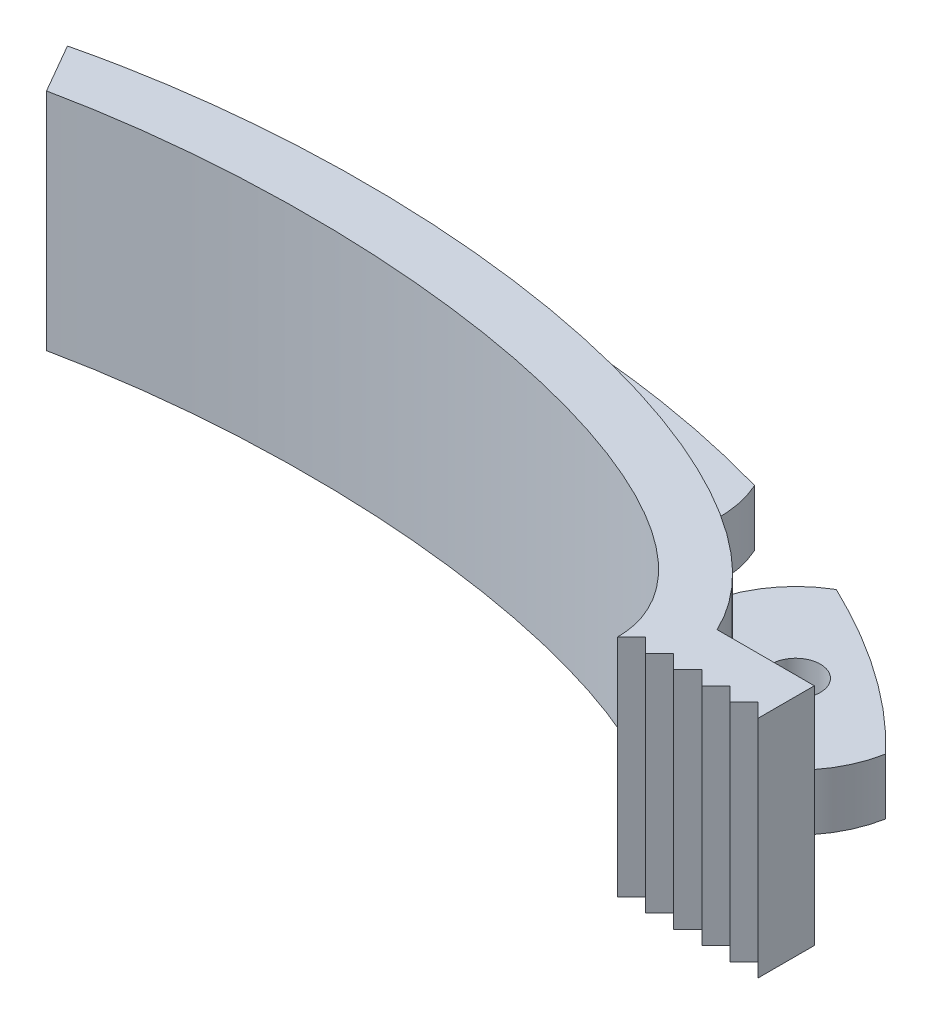
SolidWorks part; units mm, degrees
ref_plane "Спереди" through (0, 0, 0) normal (0, 0, 1) x (1, 0, 0)
ref_plane "Сверху" through (0, 0, 0) normal (0, 1, 0) x (1, 0, 0)
ref_plane "Справа" through (0, 0, 0) normal (1, 0, 0) x (0, 0, -1)
sketch "Эскиз1" plane through (0, 0, 0) normal (0, 1, 0) x (1, 0, 0)
  line L0 (0, 0) -> (56.8008, 26.4866) construction
  line L1 (0, 0) -> (22.8944, 39.6542) construction
  line L2 (0, 0) -> (-19.5543, 33.869) construction
  line L3 (0, 0) -> (57.6145, 0) construction
  line L4 (-20.1743, 18.9429) -> (-18.9654, 16.8451)
  line L5 (42.2674, 4) -> (40.0811, 4)
  circle A0 centre (33.8772, 15.7972) radius 1.75
  circle A1 centre (13.2428, 22.9372) radius 1.75
  circle A2 centre (-13.2428, 22.9372) radius 1.75
  arc A3 (-5.3565, 21.5932) -> (-20.1743, 18.9429) centre (-13.2428, 22.9372) ccw
  arc A4 (38.7397, 9.4445) -> (26.0244, 17.3244) centre (33.8772, 15.7972) ccw
  arc A6 (20.3072, 19.1829) -> (5.3565, 21.5932) centre (13.2428, 22.9372) ccw
  ellipse E0 centre (0, 0) end of major axis (45, 0) minor radius 24 construction
  ellipse E1 centre (0, 0) end of major axis (-41, 0) minor radius 19 (40.0811, 4) -> (-18.9654, 16.8451) ccw
  ellipse E2 centre (0, 0) end of major axis (43, 0) minor radius 21.7627 (-5.3565, 21.5932) -> (5.3565, 21.5932) cw
  ellipse E3 centre (0, 0) end of major axis (43, 0) minor radius 21.7627 (20.3072, 19.1829) -> (26.0244, 17.3244) cw
  ellipse E4 centre (0, 0) end of major axis (45, 0) minor radius 24 (11.5128, 23.2013) -> (14.9663, 22.6338) cw construction
  ellipse E5 centre (0, 0) end of major axis (43, 0) minor radius 21.7627 (38.7397, 9.4445) -> (42.2674, 4) cw
  dimension "D6" = 19
  dimension "D7" = 4
  dimension "D1" = 45
  dimension "D2" = 24
  dimension "D3" = 25
  dimension "D4" = 60
  dimension "D5" = 120
extrude "Бобышка-Вытянуть1" add sketch "Эскиз1" along normal blind 4
sketch "Эскиз2" plane through (0, 4, 0) normal (0, 1, 0) x (1, 0, 0)
  line L0 (37, 0) -> (47, 0) construction
  line L1 (47, 0) -> (47, 4)
  line L2 (47, 4) -> (40.0811, 4)
  line L3 (-18.9654, 16.8451) -> (-16.9427, 13.335)
  line L4 (45, 1) -> (47, 1) construction
  line L5 (47, 0) -> (46, 1)
  line L6 (46, 1) -> (45, 0)
  line L7 (44, 1) -> (43, 0)
  line L8 (45, 0) -> (44, 1)
  line L9 (42, 1) -> (41, 0)
  line L10 (43, 0) -> (42, 1)
  line L11 (40, 1) -> (39, 0)
  line L12 (41, 0) -> (40, 1)
  line L13 (38, 1) -> (37, 0)
  line L14 (39, 0) -> (38, 1)
  ellipse E0 centre (0, 0) end of major axis (-37, 0) minor radius 15 construction
  ellipse E1 centre (0, 0) end of major axis (-37, 0) minor radius 15 (37, 0) -> (-16.9427, 13.335) ccw
  ellipse E2 centre (0, 0) end of major axis (-41, 0) minor radius 19 (40.0811, 4) -> (-18.9654, 16.8451) ccw
  dimension "D5" = 4
  dimension "D1" = 4
  dimension "D2" = 10
  dimension "D3" = 37
  dimension "D4" = 15
  dimension "D6" = 1
  dimension "D7" = 5
extrude "Бобышка-Вытянуть2" add sketch "Эскиз2" along normal blind 12 and the other way blind 4 separate body
sketch "Эскиз3" plane through (0, 4, 0) normal (0, 1, 0) x (1, 0, 0)
  ellipse E0 centre (0, 0) end of major axis (-48, 0) minor radius 29
  ellipse E1 centre (0, 0) end of major axis (-67.6352, 0) minor radius 42.5614
  dimension "D1" = 29
  dimension "D2" = 48
extrude "Вырез-Вытянуть1" cut sketch "Эскиз3" against normal through all
